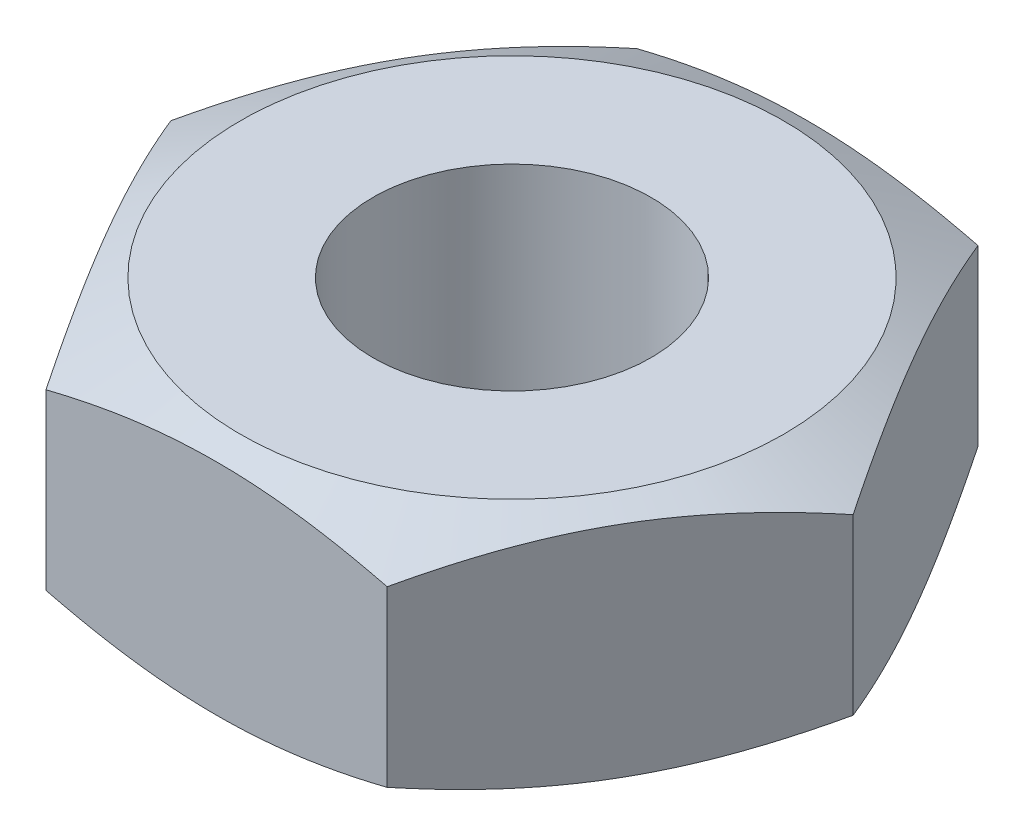
SolidWorks part; units mm, degrees
material "1023 Carbon Steel Sheet (SS)"
ref_plane "Front Plane" through (0, 0, 0) normal (0, 0, 1) x (1, 0, 0)
ref_plane "Top Plane" through (0, 0, 0) normal (0, 1, 0) x (1, 0, 0)
ref_plane "Right Plane" through (0, 0, 0) normal (1, 0, 0) x (0, 0, -1)
sketch "Sketch1" plane through (0, 0, 0) normal (0, 1, 0) x (1, 0, 0)
  line L1 (2.4537, 4.25) -> (-2.4537, 4.25)
  line L2 (-2.4537, 4.25) -> (-4.9075, 0)
  line L3 (-4.9075, 0) -> (-2.4537, -4.25)
  line L4 (-2.4537, -4.25) -> (2.4537, -4.25)
  line L5 (2.4537, -4.25) -> (4.9075, 0)
  line L6 (4.9075, 0) -> (2.4537, 4.25)
  circle A0 centre (0, 0) radius 4.25 construction
  circle A1 centre (0, 0) radius 2
  dimension "D1" = 4
  dimension "D2" = 8.5
extrude "Boss-Extrude1" add sketch "Sketch1" along normal blind 3.5
sketch "Sketch2" plane through (0, 0, 0) normal (0, 0, 1) x (1, 0, 0)
  line L0 (3.9075, 3.5) -> (4.9075, 3)
  line L2 (4.9075, 3.5) -> (4.9075, 0) construction
  line L3 (4.9075, 3) -> (4.9075, 3.5)
  line L4 (4.9075, 3.5) -> (3.9075, 3.5)
  line L5 (3.9075, 0) -> (4.9075, 0)
  line L6 (4.675, 0) -> (-4.675, 0) construction
  line L7 (4.9075, 0) -> (4.9075, 0.5)
  line L8 (4.9075, 0.5) -> (3.9075, 0)
  line L9 (0, -1000) -> (0, 49000) construction
  dimension "D1" = 2.5
  dimension "D2" = 1
revolve "Cut-Revolve1" cut sketch "Sketch2" angle 360 about L9
